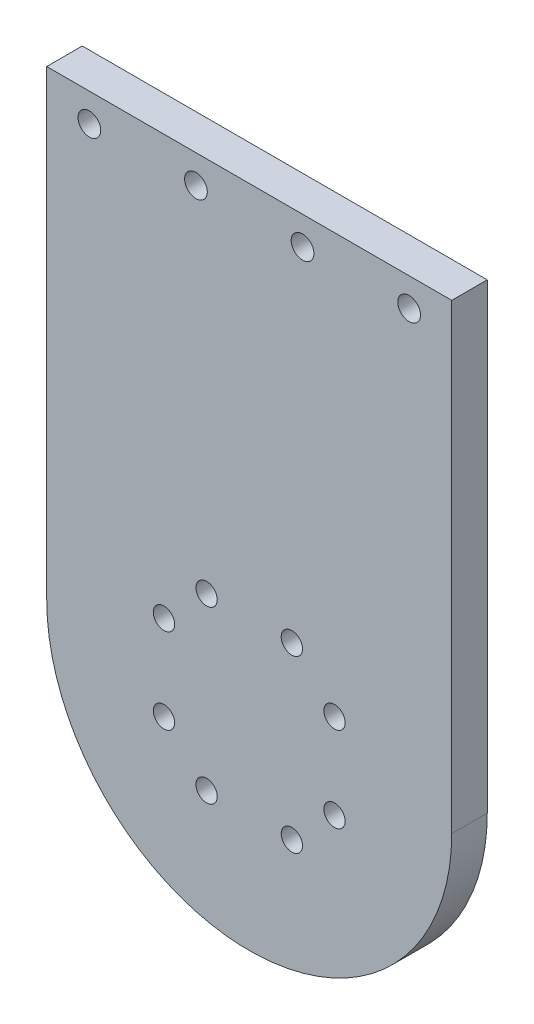
SolidWorks part; units mm, degrees
ref_plane "前基準面" through (0, 0, 0) normal (0, 0, 1) x (1, 0, 0)
ref_plane "上基準面" through (0, 0, 0) normal (0, 1, 0) x (1, 0, 0)
ref_plane "右基準面" through (0, 0, 0) normal (1, 0, 0) x (0, 0, -1)
sketch "草圖1" plane through (0, 0, 0) normal (0, 0, 1) x (1, 0, 0)
  line L0 (-28.5, 0) -> (28.5, 0)
  line L14 (28.5, 0) -> (28.5, -65)
  line L16 (-28.5, 0) -> (-28.5, -65)
  arc A2 (-28.5, -65) -> (28.5, -65) centre (0, -65) ccw
  dimension "D3" = 65
  dimension "D1" = 57
extrude "填料-伸長1" add sketch "草圖1" along normal blind 5
sketch "草圖3" plane through (0, 0, 5) normal (0, 0, 1) x (1, 0, 0)
  line L0 (-28.5, 0) -> (28.5, 0) construction
  line L1 (-28.5, 0) -> (-28.5, -65) construction
  circle A0 centre (-22.5, -4) radius 1.6
  dimension "D1" = 3.2
  dimension "D2" = 4
  dimension "D3" = 6
extrude "除料-伸長2" cut sketch "草圖3" against normal up to next
pattern_linear "直線複製排列1" count 4 spacing 15 along (1, 0, 0) of "除料-伸長2"
sketch "草圖2" plane through (0, 0, 5) normal (0, 0, 1) x (1, 0, 0)
  circle A1 centre (-6, -53) radius 1.5
  circle A2 centre (-12, -59) radius 1.5
  point P0 (0, -65)
  dimension "D1" = 6
  dimension "D2" = 3
  dimension "D4" = 6
  dimension "D3" = 12
  dimension "D5" = 12
extrude "除料-伸長1" cut sketch "草圖2" against normal up to next
pattern_circular "環狀複製排列1" count 4 over 360 about axis through (0, -65, 0) along (0, 0, 1) of "除料-伸長1"
